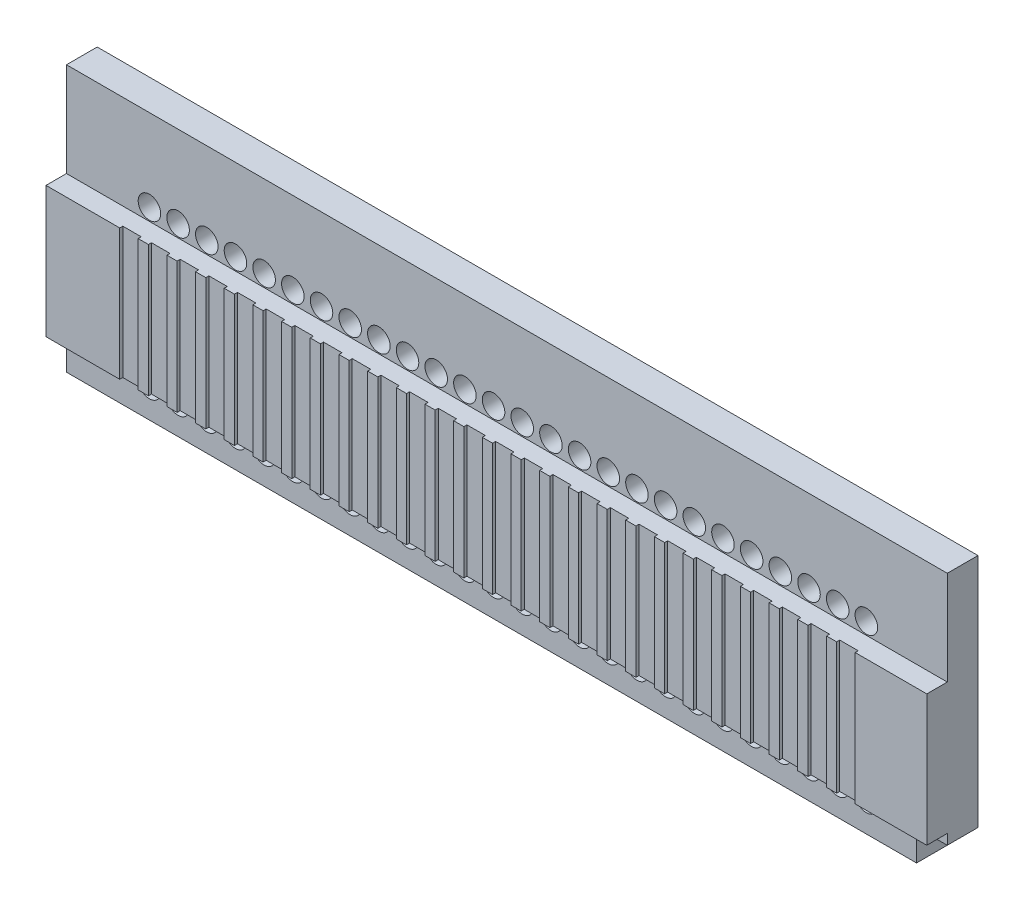
SolidWorks part; units mm, degrees
ref_plane "Plan de face" through (0, 0, 0) normal (0, 0, 1) x (1, 0, 0)
ref_plane "Plan de dessus" through (0, 0, 0) normal (0, 1, 0) x (1, 0, 0)
ref_plane "Plan de droite" through (0, 0, 0) normal (1, 0, 0) x (0, 0, -1)
sketch "Esquisse1" plane through (0, 0, 0) normal (0, 0, 1) x (1, 0, 0)
  line L1 (0, 0) -> (43, 0)
  line L2 (0, 0) -> (0, 13)
  line L3 (0, 13) -> (43, 13)
  line L4 (43, 0) -> (43, 13)
  dimension "D1" = 43
  dimension "D2" = 13
extrude "Boss.-Extru.1" add sketch "Esquisse1" along normal blind 1.5
sketch "Esquisse2" plane through (0, 0, 1.5) normal (0, 0, 1) x (1, 0, 0)
  line L0 (43, 0) -> (43, 13) construction
  line L2 (42, 2) -> (43, 2)
  line L3 (42, 2) -> (42, 8.4)
  line L4 (42, 8.4) -> (43, 8.4)
  line L5 (43, 2) -> (43, 8.4)
  line L6 (0, 0) -> (43, 0) construction
  dimension "D1" = 6.4
  dimension "D2" = 1
  dimension "D3" = 2
extrude "Boss.-Extru.2" add sketch "Esquisse2" along normal blind 1
sketch "Esquisse3" plane through (42, 0, 0) normal (-1, 0, 0) x (0, 0, 1)
  line L1 (2.5, 8.4) -> (1.5, 8.4)
  line L2 (2.5, 8.4) -> (2.5, 2)
  line L3 (2.5, 2) -> (1.5, 2)
  line L4 (1.5, 8.4) -> (1.5, 2)
extrude "Boss.-Extru.3" add sketch "Esquisse3" along normal blind 42
sketch "Esquisse8" plane through (0, 0, 0) normal (0, 0, -1) x (-1, 0, 0)
  line L1 (-43, 0) -> (-41.5, 0)
  line L2 (-43, 0) -> (-43, 1.5)
  line L3 (-43, 1.5) -> (-41.5, 1.5)
  line L4 (-41.5, 0) -> (-41.5, 1.5)
  dimension "D1" = 1.5
  dimension "D2" = 1.5
extrude "Enlèv. mat.-Extru.5" cut sketch "Esquisse8" against normal blind 4.5
sketch "Esquisse9" plane through (0, 0, 2.5) normal (0, 0, 1) x (1, 0, 0)
  line L0 (0, 2) -> (43, 2) construction
  line L1 (38.6, 2) -> (39.5, 2)
  line L2 (38.6, 2) -> (38.6, 8.4)
  line L3 (38.6, 8.4) -> (39.5, 8.4)
  line L4 (39.5, 2) -> (39.5, 8.4)
  line L5 (43, 8.4) -> (0, 8.4) construction
  line L8 (43, 2) -> (43, 8.4) construction
  dimension "D1" = 0.9
  dimension "D2" = 3.5
extrude "Enlèv. mat.-Extru.6" cut sketch "Esquisse9" against normal blind 0.15 contours L4 L3 L2 L1
pattern_linear "Répétition linéaire4" count 26 spacing 1.4 along (-1, 0, 0) of "Enlèv. mat.-Extru.6"
sketch "Esquisse10" plane through (0, 0, 1.5) normal (0, 0, 1) x (1, 0, 0)
  line L0 (43, 13) -> (0, 13) construction
  line L2 (39.05, 9) -> (39.05, 13) construction
  line L5 (38.6, 8.4) -> (39.5, 8.4) construction
  circle A0 centre (39.05, 9) radius 0.55
  point P6 (39.05, 8.4)
  dimension "D1" = 1.1
  dimension "D2" = 4
  dimension "D3" = 0
extrude "Enlèv. mat.-Extru.8" cut sketch "Esquisse10" against normal through all
pattern_linear "Répétition linéaire5" count 26 spacing 1.4 along (-1, 0, 0) of "Enlèv. mat.-Extru.8"
sketch "Esquisse11" plane through (0, 0, 1.5) normal (0, 0, 1) x (1, 0, 0)
  line L0 (43, 1.5) -> (43, 2) construction
  line L1 (0, 2) -> (43, 2) construction
  circle A0 centre (39.05, 1.45) radius 0.55
  dimension "D2" = 1.1
  dimension "D1" = 3.95
  dimension "D3" = 0.55
extrude "Enlèv. mat.-Extru.9" cut sketch "Esquisse11" against normal blind 7.3
pattern_linear "Répétition linéaire6" count 26 spacing 1.4 along (-1, 0, 0) of "Enlèv. mat.-Extru.9"
